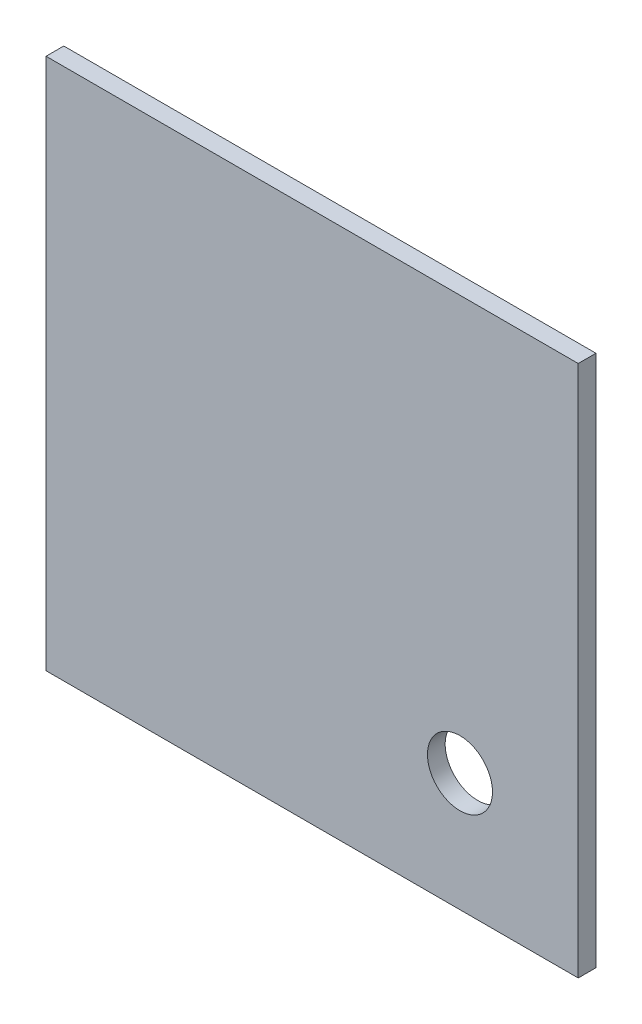
SolidWorks part; units mm, degrees
ref_plane "Front Plane" through (0, 0, 0) normal (0, 0, 1) x (1, 0, 0)
ref_plane "Top Plane" through (0, 0, 0) normal (0, 1, 0) x (1, 0, 0)
ref_plane "Right Plane" through (0, 0, 0) normal (1, 0, 0) x (0, 0, -1)
sketch "Sketch1" plane through (0, 0, 0) normal (0, 0, 1) x (1, 0, 0)
  line L0 (25, 45) -> (25, -45) construction
  line L1 (45, -45) -> (-45, -45)
  line L2 (45, -45) -> (45, 45)
  line L3 (45, 45) -> (-45, 45)
  line L4 (-45, -45) -> (-45, 45)
  line L5 (45, -45) -> (-45, 45) construction
  line L6 (45, 45) -> (-45, -45) construction
  line L7 (-45, -25) -> (45, -25) construction
  circle A0 centre (25, -25) radius 5.5
  point P0 (0, 0)
  dimension "D5" = 11
  dimension "D1" = 90
  dimension "D2" = 90
  dimension "D3" = 70
  dimension "D4" = 70
extrude "Boss-Extrude1" add sketch "Sketch1" along normal blind 3
